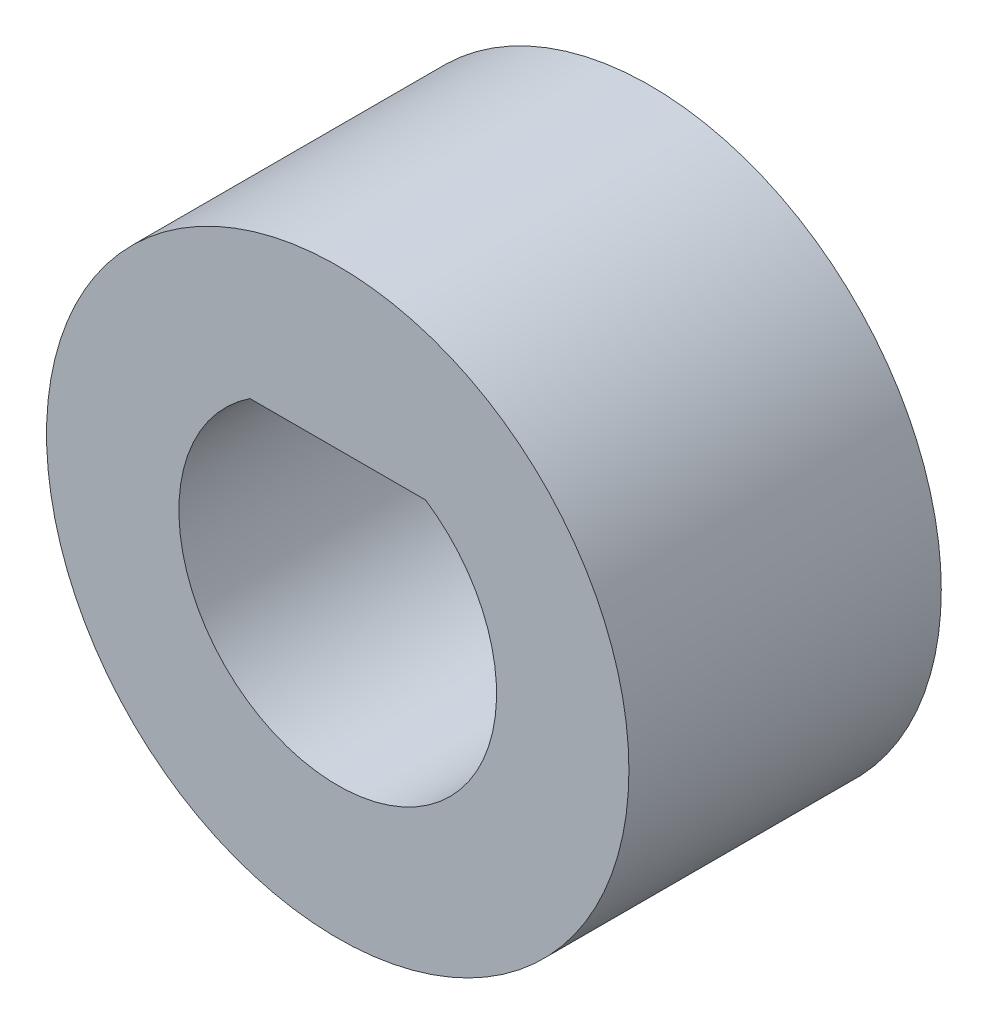
SolidWorks part; units mm, degrees
material "2A12"
ref_plane "前视基准面" through (0, 0, 0) normal (0, 0, 1) x (1, 0, 0)
ref_plane "上视基准面" through (0, 0, 0) normal (0, 1, 0) x (1, 0, 0)
ref_plane "右视基准面" through (0, 0, 0) normal (1, 0, 0) x (0, 0, -1)
sketch "草图1" plane through (0, 0, 0) normal (0, 0, 1) x (1, 0, 0)
  line L0 (-0.8292, 1.25) -> (0.8292, 1.25)
  circle A0 centre (0, 0) radius 2.75
  arc A1 (-0.8292, 1.25) -> (0.8292, 1.25) centre (0, 0) ccw
  dimension "D1" = 3
  dimension "D2" = 5.5
  dimension "D3" = 1.25
extrude "凸台-拉伸1" add sketch "草图1" along normal blind 2.95
